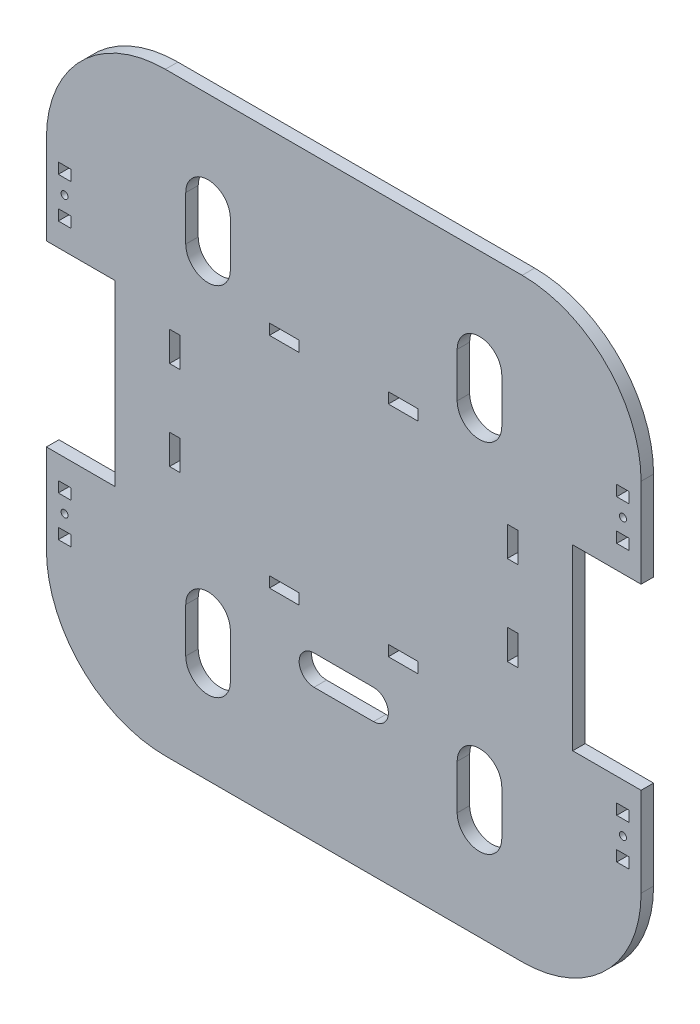
SolidWorks part; units mm, degrees
material "Oak"
ref_plane "Front Plane" through (0, 0, 0) normal (0, 0, 1) x (1, 0, 0)
ref_plane "Top Plane" through (0, 0, 0) normal (0, 1, 0) x (1, 0, 0)
ref_plane "Right Plane" through (0, 0, 0) normal (1, 0, 0) x (0, 0, -1)
sketch "Sketch1" plane through (0, 0, 0) normal (0, 0, 1) x (1, 0, 0)
  line L1 (50.8, 0) -> (203.2, 0)
  line L2 (0, 50.8) -> (0, 203.2)
  line L3 (50.8, 254) -> (203.2, 254)
  line L4 (254, 50.8) -> (254, 203.2)
  arc A0 (0, 203.2) -> (50.8, 254) centre (50.8, 203.2) cw
  arc A1 (254, 203.2) -> (203.2, 254) centre (203.2, 203.2) ccw
  arc A2 (0, 50.8) -> (50.8, 0) centre (50.8, 50.8) ccw
  arc A3 (254, 50.8) -> (203.2, 0) centre (203.2, 50.8) cw
  point P9 (254, 254)
  point P12 (0, 0)
  point P15 (254, 0)
  dimension "D3" = 50.8
  dimension "D4" = 50.8
  dimension "D5" = 50.8
  dimension "D6" = 50.8
  dimension "D1" = 254
  dimension "D2" = 254
extrude "Boss-Extrude1" add sketch "Sketch1" along normal blind 5.334
sketch "Sketch3" plane through (0, 0, 5.334) normal (0, 0, 1) x (1, 0, 0)
  line L0 (29.21, 95.25) -> (29.21, 88.9)
  line L5 (203.2, 254) -> (50.8, 254) construction
  line L6 (29.21, 120.65) -> (29.21, 107.95)
  line L11 (0, 203.2) -> (0, 50.8) construction
  line L60 (0, 165.1) -> (29.21, 165.1)
  line L61 (0, 165.1) -> (0, 88.9)
  line L62 (0, 88.9) -> (29.21, 88.9)
  line L63 (29.21, 165.1) -> (29.21, 158.75)
  line L64 (254, 50.8) -> (254, 203.2) construction
  line L65 (254, 165.1) -> (224.79, 165.1)
  line L66 (254, 165.1) -> (254, 88.9)
  line L67 (254, 88.9) -> (224.79, 88.9)
  line L68 (224.79, 165.1) -> (224.79, 158.75)
  line L69 (29.21, 146.05) -> (29.21, 133.35)
  line L70 (224.79, 146.05) -> (224.79, 133.35)
  line L71 (224.79, 120.65) -> (224.79, 107.95)
  line L72 (224.79, 95.25) -> (224.79, 88.9)
  line L73 (224.79, 158.75) -> (224.79, 146.05)
  line L74 (224.79, 133.35) -> (224.79, 120.65)
  line L75 (224.79, 107.95) -> (224.79, 95.25)
  line L76 (29.21, 158.75) -> (29.21, 146.05)
  line L77 (29.21, 133.35) -> (29.21, 120.65)
  line L78 (29.21, 107.95) -> (29.21, 95.25)
  dimension "D5" = 76.2
  dimension "D6" = 29.21
  dimension "D36" = 88.9
  dimension "D50" = 29.21
  dimension "D51" = 76.2
  dimension "D52" = 88.9
extrude "Cut-Extrude1" cut sketch "Sketch3" against normal blind 5.334
sketch "Sketch6" plane through (0, 0, 5.334) normal (0, 0, 1) x (1, 0, 0)
  line L0 (29.21, 127) -> (224.79, 127) construction
  line L3 (127, 254) -> (127, 0) construction
  line L4 (203.2, 254) -> (50.8, 254) construction
  line L5 (50.8, 0) -> (203.2, 0) construction
  line L6 (0, 203.2) -> (0, 165.1) construction
  line L7 (5.08, 196.85) -> (10.414, 196.85)
  line L8 (5.08, 196.85) -> (5.08, 192.278)
  line L9 (5.08, 192.278) -> (10.414, 192.278)
  line L10 (10.414, 196.85) -> (10.414, 192.278)
  line L11 (5.08, 196.85) -> (10.414, 192.278) construction
  line L12 (5.08, 192.278) -> (10.414, 196.85) construction
  line L13 (5.08, 175.006) -> (10.414, 175.006)
  line L14 (5.08, 175.006) -> (5.08, 179.578)
  line L15 (5.08, 179.578) -> (10.414, 179.578)
  line L16 (10.414, 175.006) -> (10.414, 179.578)
  line L17 (5.08, 175.006) -> (10.414, 179.578) construction
  line L18 (5.08, 179.578) -> (10.414, 175.006) construction
  line L19 (248.92, 179.578) -> (243.586, 175.006) construction
  line L20 (248.92, 175.006) -> (243.586, 179.578) construction
  line L21 (248.92, 192.278) -> (243.586, 196.85) construction
  line L22 (248.92, 196.85) -> (243.586, 192.278) construction
  line L23 (243.586, 175.006) -> (243.586, 179.578)
  line L24 (248.92, 179.578) -> (243.586, 179.578)
  line L25 (248.92, 175.006) -> (248.92, 179.578)
  line L26 (248.92, 175.006) -> (243.586, 175.006)
  line L27 (243.586, 196.85) -> (243.586, 192.278)
  line L28 (248.92, 192.278) -> (243.586, 192.278)
  line L29 (248.92, 196.85) -> (248.92, 192.278)
  line L30 (248.92, 196.85) -> (243.586, 196.85)
  line L31 (248.92, 57.15) -> (243.586, 61.722) construction
  line L32 (248.92, 61.722) -> (243.586, 57.15) construction
  line L33 (248.92, 78.994) -> (243.586, 74.422) construction
  line L34 (248.92, 74.422) -> (243.586, 78.994) construction
  line L35 (5.08, 74.422) -> (10.414, 78.994) construction
  line L36 (5.08, 78.994) -> (10.414, 74.422) construction
  line L37 (5.08, 61.722) -> (10.414, 57.15) construction
  line L38 (5.08, 57.15) -> (10.414, 61.722) construction
  line L39 (248.92, 57.15) -> (243.586, 57.15)
  line L40 (248.92, 57.15) -> (248.92, 61.722)
  line L41 (248.92, 61.722) -> (243.586, 61.722)
  line L42 (243.586, 57.15) -> (243.586, 61.722)
  line L43 (248.92, 78.994) -> (243.586, 78.994)
  line L44 (248.92, 78.994) -> (248.92, 74.422)
  line L45 (248.92, 74.422) -> (243.586, 74.422)
  line L46 (243.586, 78.994) -> (243.586, 74.422)
  line L47 (10.414, 78.994) -> (10.414, 74.422)
  line L48 (5.08, 74.422) -> (10.414, 74.422)
  line L49 (5.08, 78.994) -> (5.08, 74.422)
  line L50 (5.08, 78.994) -> (10.414, 78.994)
  line L51 (10.414, 57.15) -> (10.414, 61.722)
  line L52 (5.08, 61.722) -> (10.414, 61.722)
  line L53 (5.08, 57.15) -> (5.08, 61.722)
  line L54 (5.08, 57.15) -> (10.414, 57.15)
  line L55 (29.21, 88.9) -> (29.21, 165.1) construction
  line L56 (224.79, 165.1) -> (224.79, 88.9) construction
  circle A0 centre (7.747, 185.928) radius 1.5
  circle A1 centre (246.253, 185.928) radius 1.5
  circle A2 centre (246.253, 68.072) radius 1.5
  circle A3 centre (7.747, 68.072) radius 1.5
  point P12 (7.747, 194.564)
  point P17 (7.747, 177.292)
  point P37 (246.253, 177.292)
  point P38 (246.253, 194.564)
  point P59 (246.253, 59.436)
  point P60 (246.253, 76.708)
  point P61 (7.747, 76.708)
  point P62 (7.747, 59.436)
  dimension "D10" = 3
  dimension "D1" = 5.334
  dimension "D2" = 4.572
  dimension "D3" = 6.35
  dimension "D4" = 4.572
  dimension "D5" = 12.7
  dimension "D6" = 5.334
  dimension "D7" = 5.08
  dimension "D8" = 5.08
  dimension "D9" = 6.35
  dimension "D11" = 2.667
extrude "Cut-Extrude4" cut sketch "Sketch6" against normal through all
sketch "Sketch7" plane through (0, 0, 5.334) normal (0, 0, 1) x (1, 0, 0)
  line L0 (69.0308, 60.325) -> (69.0308, 41.275) construction
  line L1 (78.5558, 60.325) -> (78.5558, 41.275)
  line L2 (59.5058, 60.325) -> (59.5058, 41.275)
  line L3 (50.8, 0) -> (203.2, 0) construction
  line L6 (29.21, 127) -> (224.79, 127) construction
  line L7 (29.21, 88.9) -> (29.21, 165.1) construction
  line L8 (224.79, 165.1) -> (224.79, 88.9) construction
  line L9 (127, 254) -> (127, 0) construction
  line L10 (203.2, 254) -> (50.8, 254) construction
  line L11 (184.9692, 60.325) -> (184.9692, 41.275) construction
  line L12 (175.4442, 60.325) -> (175.4442, 41.275)
  line L13 (194.4942, 60.325) -> (194.4942, 41.275)
  line L14 (184.9692, 193.675) -> (184.9692, 212.725) construction
  line L15 (175.4442, 193.675) -> (175.4442, 212.725)
  line L16 (194.4942, 193.675) -> (194.4942, 212.725)
  line L17 (69.0308, 193.675) -> (69.0308, 212.725) construction
  line L18 (78.5558, 193.675) -> (78.5558, 212.725)
  line L19 (59.5058, 193.675) -> (59.5058, 212.725)
  arc A0 (78.5558, 60.325) -> (59.5058, 60.325) centre (69.0308, 60.325) ccw
  arc A1 (59.5058, 41.275) -> (78.5558, 41.275) centre (69.0308, 41.275) ccw
  arc A4 (175.4442, 60.325) -> (194.4942, 60.325) centre (184.9692, 60.325) cw
  arc A5 (194.4942, 41.275) -> (175.4442, 41.275) centre (184.9692, 41.275) cw
  arc A6 (175.4442, 193.675) -> (194.4942, 193.675) centre (184.9692, 193.675) ccw
  arc A7 (194.4942, 212.725) -> (175.4442, 212.725) centre (184.9692, 212.725) ccw
  arc A8 (78.5558, 193.675) -> (59.5058, 193.675) centre (69.0308, 193.675) cw
  arc A9 (59.5058, 212.725) -> (78.5558, 212.725) centre (69.0308, 212.725) cw
  point P2 (69.0308, 50.8)
  point P21 (184.9692, 50.8)
  point P28 (184.9692, 203.2)
  point P35 (69.0308, 203.2)
  dimension "D1" = 19.05
  dimension "D2" = 50.8
  dimension "D3" = 19.05
extrude "Cut-Extrude5" cut sketch "Sketch7" against normal through all
sketch "Sketch8" plane through (0, 0, 5.334) normal (0, 0, 1) x (1, 0, 0)
  line L0 (114.3, 63.5) -> (139.7, 63.5) construction
  line L1 (114.3, 69.85) -> (139.7, 69.85)
  line L2 (114.3, 57.15) -> (139.7, 57.15)
  line L3 (127, 0) -> (127, 254) construction
  line L4 (50.8, 0) -> (203.2, 0) construction
  line L5 (203.2, 254) -> (50.8, 254) construction
  arc A0 (114.3, 69.85) -> (114.3, 57.15) centre (114.3, 63.5) ccw
  arc A1 (139.7, 57.15) -> (139.7, 69.85) centre (139.7, 63.5) ccw
  point P2 (127, 63.5)
  dimension "D1" = 12.7
  dimension "D2" = 25.4
  dimension "D3" = 0
  dimension "D4" = 63.5
extrude "Cut-Extrude6" cut sketch "Sketch8" against normal blind 7.62 contours L2 A1 L1 A0
sketch "Sketch11" plane through (0, 0, 5.334) normal (0, 0, 1) x (1, 0, 0)
  line L0 (203.2, 254) -> (50.8, 254) construction
  line L1 (57.15, 88.9) -> (196.85, 88.9)
  line L2 (57.15, 88.9) -> (57.15, 177.8)
  line L3 (57.15, 177.8) -> (196.85, 177.8)
  line L4 (196.85, 88.9) -> (196.85, 177.8)
  line L5 (57.15, 88.9) -> (196.85, 177.8) construction
  line L6 (57.15, 177.8) -> (196.85, 88.9) construction
  line L8 (94.6851, 177.8) -> (113.3989, 177.8)
  line L12 (137.7025, 177.8) -> (158.6036, 177.8)
  line L16 (57.15, 158.75) -> (52.578, 158.75)
  line L17 (57.15, 158.75) -> (57.15, 146.05)
  line L18 (57.15, 146.05) -> (52.578, 146.05)
  line L19 (52.578, 158.75) -> (52.578, 146.05)
  line L20 (57.15, 120.65) -> (52.578, 120.65)
  line L21 (57.15, 120.65) -> (57.15, 107.95)
  line L22 (57.15, 107.95) -> (52.578, 107.95)
  line L23 (52.578, 120.65) -> (52.578, 107.95)
  line L24 (95.25, 88.9) -> (107.95, 88.9)
  line L25 (95.25, 88.9) -> (95.25, 84.328)
  line L26 (95.25, 84.328) -> (107.95, 84.328)
  line L27 (107.95, 88.9) -> (107.95, 84.328)
  line L28 (146.05, 88.9) -> (158.75, 88.9)
  line L29 (146.05, 88.9) -> (146.05, 84.328)
  line L30 (146.05, 84.328) -> (158.75, 84.328)
  line L31 (158.75, 88.9) -> (158.75, 84.328)
  line L33 (196.85, 161.3827) -> (196.85, 145.5)
  line L38 (196.85, 126.1899) -> (196.85, 108.5)
  line L43 (95.25, 177.8) -> (107.95, 177.8)
  line L44 (95.25, 177.8) -> (95.25, 182.372)
  line L45 (95.25, 182.372) -> (107.95, 182.372)
  line L46 (107.95, 177.8) -> (107.95, 182.372)
  line L47 (146.05, 177.8) -> (158.75, 177.8)
  line L48 (146.05, 177.8) -> (146.05, 182.372)
  line L49 (146.05, 182.372) -> (158.75, 182.372)
  line L50 (158.75, 177.8) -> (158.75, 182.372)
  line L51 (196.85, 158.75) -> (201.422, 158.75)
  line L52 (196.85, 158.75) -> (196.85, 146.05)
  line L53 (196.85, 146.05) -> (201.422, 146.05)
  line L54 (201.422, 158.75) -> (201.422, 146.05)
  line L55 (196.85, 120.65) -> (201.422, 120.65)
  line L56 (196.85, 120.65) -> (196.85, 107.95)
  line L57 (196.85, 107.95) -> (201.422, 107.95)
  line L58 (201.422, 120.65) -> (201.422, 107.95)
  point P0 (127, 133.35)
  point P8 (54.864, 120.65)
  point P9 (127, 254)
  dimension "D1" = 139.7
  dimension "D2" = 88.9
  dimension "D3" = 76.2
  dimension "D4" = 4.572
  dimension "D5" = 4.572
  dimension "D6" = 12.7
  dimension "D7" = 38.1
  dimension "D8" = 12.7
  dimension "D9" = 38.1
  dimension "D10" = 12.7
  dimension "D11" = 4.572
  dimension "D12" = 4.572
  dimension "D13" = 19.05
  dimension "D14" = 19.05
  dimension "D15" = 12.7
  dimension "D16" = 4.572
  dimension "D17" = 12.7
  dimension "D18" = 38.1
  dimension "D19" = 4.572
  dimension "D20" = 12.7
  dimension "D21" = 38.1
  dimension "D22" = 4.572
  dimension "D23" = 12.7
  dimension "D24" = 19.05
  dimension "D25" = 12.7
  dimension "D26" = 4.572
  dimension "D27" = 19.05
extrude "Cut-Extrude9" cut sketch "Sketch11" against normal through all contours L3 L50 L49 L48 L12 | L8 L46 L45 L44 | L54 L51 L33 L53 | L58 L55 L4 L57 | L31 L1 L29 L30 | L27 L1 L25 L26 | L20 L23 L22 L2 | L16 L19 L18 L2
equation "\"Base_Width\"= 10in"
equation "\"Base_Length\"= 10in"
equation "\"Wheel_Width\"= 3in"
equation "\"MDF\"= 0.21in"
equation "\"D1@Sketch1\"=\"Base_Width\""
equation "\"D2@Sketch1\"=\"Base_Length\""
equation "\"D1@Boss-Extrude1\"=\"MDF\""
equation "\"D1@Cut-Extrude1\"=\"MDF\""
equation "\"D5@Sketch3\"=\"Wheel_Width\""
equation "\"D36@Sketch3\"=\"Base_Length\"/2 -\"Wheel_Width\"/2"
equation "\"D51@Sketch3\"=\"Wheel_Width\""
equation "\"D52@Sketch3\"=\"Base_Length\"/2 -\"Wheel_Width\"/2"
